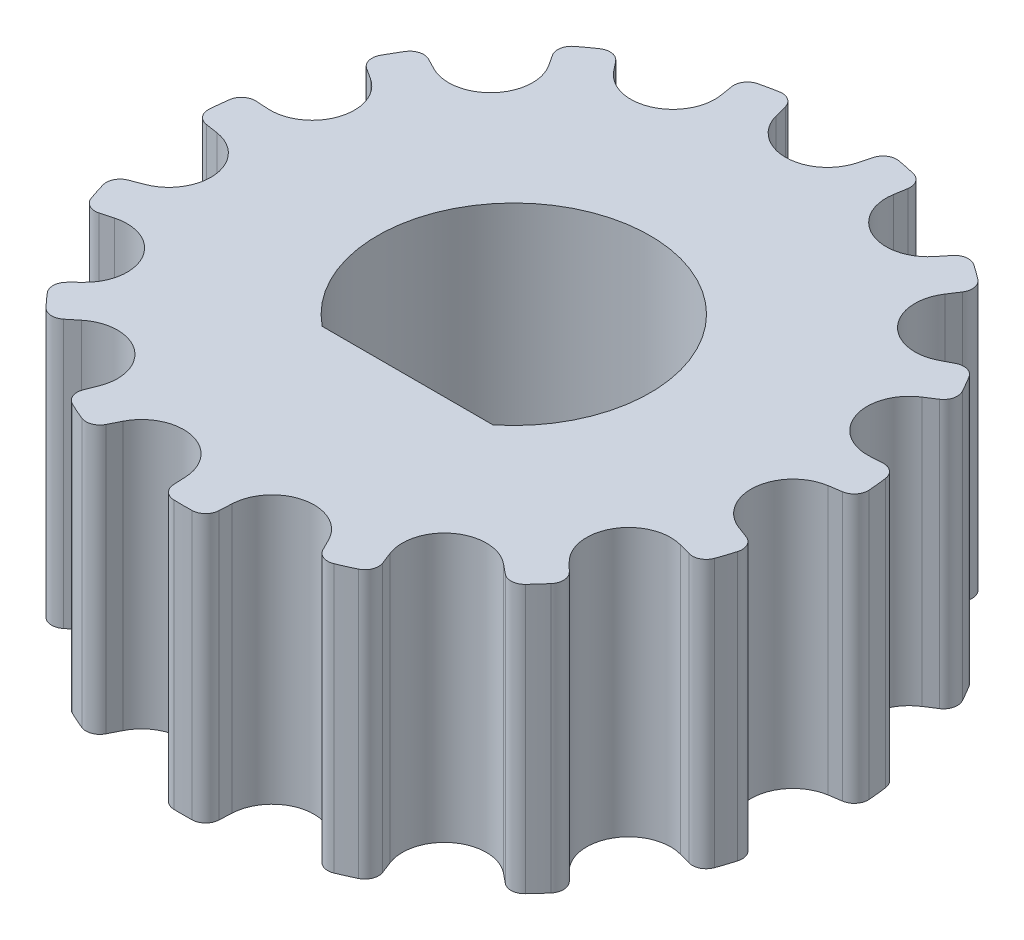
SolidWorks part; units mm, degrees
ref_plane "Front Plane" through (0, 0, 0) normal (0, 0, 1) x (1, 0, 0)
ref_plane "Top Plane" through (0, 0, 0) normal (0, 1, 0) x (1, 0, 0)
ref_plane "Right Plane" through (0, 0, 0) normal (1, 0, 0) x (0, 0, -1)
sketch "Sketch1" plane through (0, 0, 0) normal (0, 1, 0) x (1, 0, 0)
  circle A0 centre (0, 0) radius 7.162
  dimension "D1" = 14.3239
extrude "Boss-Extrude1" add sketch "Sketch1" along normal blind 5.8
sketch "Sketch2" plane through (0, 5.8, 0) normal (0, 1, 0) x (1, 0, 0)
  line L0 (0, 0) -> (0, 7.162) construction
  line L1 (-0.8799, 6.5598) -> (-0.95, 6.8255)
  line L2 (-2.913, 6.5428) -> (-2.913, 7.162)
  line L3 (-2.913, 7.162) -> (2.913, 7.162)
  line L4 (0.8799, 6.5598) -> (0.95, 6.8255)
  line L5 (2.913, 6.5428) -> (2.913, 7.162)
  circle A0 centre (0, 0) radius 7.162 construction
  arc A1 (0.8799, 6.5598) -> (-0.8799, 6.5598) centre (0, 6.792) cw
  arc A2 (-0.95, 6.8255) -> (-1.2943, 7.0441) centre (-1.2401, 6.749) ccw
  arc A4 (0.95, 6.8255) -> (1.2943, 7.0441) centre (1.2401, 6.749) cw
  arc A5 (-1.2943, 7.0441) -> (-2.913, 6.5428) centre (0, 0) ccw
  arc A6 (1.2943, 7.0441) -> (2.913, 6.5428) centre (0, 0) cw
  point P11 (0, 7.162)
  point P19 (0, 5.882)
  dimension "D3" = 0.3
  dimension "D5" = 0.91
  dimension "D2" = 0.95
  dimension "D4" = 1.28
  dimension "D6" = 24
extrude "Cut-Extrude1" cut sketch "Sketch2" against normal through all
pattern_circular "CirPattern1" count 15 over 360 about axis through (0, 0, 0) along (0, 1, 0) of "Cut-Extrude1"
sketch "Sketch3" plane through (0, 0, 0) normal (0, -1, 0) x (1, 0, 0)
  line L0 (1.8473, 2.3) -> (-1.8473, 2.3)
  arc A0 (-1.8473, 2.3) -> (1.8473, 2.3) centre (0, 0) ccw
  dimension "D1" = 5.9
  dimension "D2" = 2.3
extrude "Cut-Extrude2" cut sketch "Sketch3" against normal through all
sketch "Sketch5" plane through (0, 0, 0) normal (0, -1, 0) x (1, 0, 0)
  line L60 (5.4179, -3.8244) -> (5.6623, -3.9501)
  line L61 (6.252, -2.9286) -> (6.021, -2.7798)
  line L62 (6.505, -1.2901) -> (6.7794, -1.3055)
  line L63 (6.9027, -0.1325) -> (6.6311, -0.0906)
  line L64 (6.4674, 1.4673) -> (6.7243, 1.5648)
  line L65 (6.3598, 2.6865) -> (6.0946, 2.6144)
  line L66 (5.3115, 3.9709) -> (5.5065, 4.1645)
  line L67 (4.7173, 5.041) -> (4.5044, 4.8673)
  line L68 (3.2371, 5.788) -> (3.3366, 6.0442)
  line L69 (2.2591, 6.5239) -> (2.1352, 6.2786)
  line L70 (0.6031, 6.6042) -> (0.5897, 6.8787)
  line L71 (-0.5897, 6.8787) -> (-0.6031, 6.6042)
  line L72 (-2.1352, 6.2786) -> (-2.2591, 6.5239)
  line L73 (-3.3366, 6.0442) -> (-3.2371, 5.788)
  line L74 (-4.5044, 4.8673) -> (-4.7173, 5.041)
  line L75 (-5.5065, 4.1645) -> (-5.3115, 3.9709)
  line L76 (-6.0946, 2.6144) -> (-6.3598, 2.6865)
  line L77 (-6.7243, 1.5648) -> (-6.4674, 1.4673)
  line L78 (-6.6311, -0.0906) -> (-6.9027, -0.1325)
  line L79 (-6.7794, -1.3055) -> (-6.505, -1.2901)
  line L80 (-6.021, -2.7798) -> (-6.252, -2.9286)
  line L81 (-5.6623, -3.9501) -> (-5.4179, -3.8244)
  line L82 (-4.3698, -4.9885) -> (-4.5203, -5.2184)
  line L83 (-3.5661, -5.9117) -> (-3.394, -5.6974)
  line L84 (-1.963, -6.3345) -> (-2.007, -6.6058)
  line L85 (-0.8533, -6.851) -> (-0.7832, -6.5853)
  line L86 (0.7832, -6.5853) -> (0.8533, -6.851)
  line L87 (2.007, -6.6058) -> (1.963, -6.3345)
  line L88 (3.394, -5.6974) -> (3.5661, -5.9117)
  line L89 (4.5203, -5.2184) -> (4.3698, -4.9885)
  line L90 (5.4179, -3.8244) -> (5.6623, -3.9501)
  line L91 (6.252, -2.9286) -> (6.021, -2.7798)
  line L92 (6.505, -1.2901) -> (6.7794, -1.3055)
  line L93 (6.9027, -0.1325) -> (6.6311, -0.0906)
  line L94 (6.4674, 1.4673) -> (6.7243, 1.5648)
  line L95 (6.3598, 2.6865) -> (6.0946, 2.6144)
  line L96 (5.3115, 3.9709) -> (5.5065, 4.1645)
  line L97 (4.7173, 5.041) -> (4.5044, 4.8673)
  line L98 (3.2371, 5.788) -> (3.3366, 6.0442)
  line L99 (2.2591, 6.5239) -> (2.1352, 6.2786)
  line L100 (0.6031, 6.6042) -> (0.5897, 6.8787)
  line L101 (-0.5897, 6.8787) -> (-0.6031, 6.6042)
  line L102 (-2.1352, 6.2786) -> (-2.2591, 6.5239)
  line L103 (-3.3366, 6.0442) -> (-3.2371, 5.788)
  line L104 (-4.5044, 4.8673) -> (-4.7173, 5.041)
  line L105 (-5.5065, 4.1645) -> (-5.3115, 3.9709)
  line L106 (-6.0946, 2.6144) -> (-6.3598, 2.6865)
  line L107 (-6.7243, 1.5648) -> (-6.4674, 1.4673)
  line L108 (-6.6311, -0.0906) -> (-6.9027, -0.1325)
  line L109 (-6.7794, -1.3055) -> (-6.505, -1.2901)
  line L110 (-6.021, -2.7798) -> (-6.252, -2.9286)
  line L111 (-5.6623, -3.9501) -> (-5.4179, -3.8244)
  line L112 (-4.3698, -4.9885) -> (-4.5203, -5.2184)
  line L113 (-3.5661, -5.9117) -> (-3.394, -5.6974)
  line L114 (-1.963, -6.3345) -> (-2.007, -6.6058)
  line L115 (-0.8533, -6.851) -> (-0.7832, -6.5853)
  line L116 (0.7832, -6.5853) -> (0.8533, -6.851)
  line L117 (2.007, -6.6058) -> (1.963, -6.3345)
  line L118 (3.394, -5.6974) -> (3.5661, -5.9117)
  line L119 (4.5203, -5.2184) -> (4.3698, -4.9885)
  circle A60 centre (0, 0) radius 3.9038
  arc A120 (5.6623, -3.9501) -> (6.186, -3.8039) centre (5.8452, -3.5944) ccw
  arc A121 (6.186, -3.8039) -> (6.3873, -3.4553) centre (0, 0) ccw
  arc A122 (6.3873, -3.4553) -> (6.252, -2.9286) centre (6.0355, -3.2649) ccw
  arc A123 (6.505, -1.2901) -> (6.021, -2.7798) centre (6.4595, -2.0988) ccw
  arc A124 (6.7794, -1.3055) -> (7.1984, -0.959) centre (6.8019, -0.9062) ccw
  arc A125 (7.1984, -0.959) -> (7.2405, -0.5586) centre (0, 0) ccw
  arc A126 (7.2405, -0.5586) -> (6.9027, -0.1325) centre (6.8416, -0.5278) ccw
  arc A127 (6.4674, 1.4673) -> (6.6311, -0.0906) centre (6.7548, 0.71) ccw
  arc A128 (6.7243, 1.5648) -> (6.9661, 2.0518) centre (6.5824, 1.9387) ccw
  arc A129 (6.9661, 2.0518) -> (6.8417, 2.4347) centre (0, 0) ccw
  arc A130 (6.8417, 2.4347) -> (6.3598, 2.6865) centre (6.4648, 2.3006) ccw
  arc A131 (5.3115, 3.9709) -> (6.0946, 2.6144) centre (5.882, 3.396) ccw
  arc A132 (5.5065, 4.1645) -> (5.5293, 4.7077) centre (5.2248, 4.4484) ccw
  arc A133 (5.5293, 4.7077) -> (5.2599, 5.0069) centre (0, 0) ccw
  arc A134 (5.2599, 5.0069) -> (4.7173, 5.041) centre (4.9702, 4.7312) ccw
  arc A135 (3.2371, 5.788) -> (4.5044, 4.8673) centre (3.9922, 5.4948) ccw
  arc A136 (3.3366, 6.0442) -> (3.1365, 6.5497) centre (2.9637, 6.1889) ccw
  arc A137 (3.1365, 6.5497) -> (2.7687, 6.7135) centre (0, 0) ccw
  arc A138 (2.7687, 6.7135) -> (2.2591, 6.5239) centre (2.6162, 6.3437) ccw
  arc A139 (0.6031, 6.6042) -> (2.1352, 6.2786) centre (1.4121, 6.6436) ccw
  arc A140 (0.5897, 6.8787) -> (0.2013, 7.2592) centre (0.1902, 6.8593) ccw
  arc A141 (0.2013, 7.2592) -> (-0.2013, 7.2592) centre (0, 0) ccw
  arc A142 (-0.2013, 7.2592) -> (-0.5897, 6.8787) centre (-0.1902, 6.8593) ccw
  arc A143 (-2.1352, 6.2786) -> (-0.6031, 6.6042) centre (-1.4121, 6.6436) ccw
  arc A144 (-2.2591, 6.5239) -> (-2.7687, 6.7135) centre (-2.6162, 6.3437) ccw
  arc A145 (-2.7687, 6.7135) -> (-3.1365, 6.5497) centre (0, 0) ccw
  arc A146 (-3.1365, 6.5497) -> (-3.3366, 6.0442) centre (-2.9637, 6.1889) ccw
  arc A147 (-4.5044, 4.8673) -> (-3.2371, 5.788) centre (-3.9922, 5.4948) ccw
  arc A148 (-4.7173, 5.041) -> (-5.2599, 5.0069) centre (-4.9702, 4.7312) ccw
  arc A149 (-5.2599, 5.0069) -> (-5.5293, 4.7077) centre (0, 0) ccw
  arc A150 (-5.5293, 4.7077) -> (-5.5065, 4.1645) centre (-5.2248, 4.4484) ccw
  arc A151 (-6.0946, 2.6144) -> (-5.3115, 3.9709) centre (-5.882, 3.396) ccw
  arc A152 (-6.3598, 2.6865) -> (-6.8417, 2.4347) centre (-6.4648, 2.3006) ccw
  arc A153 (-6.8417, 2.4347) -> (-6.9661, 2.0518) centre (0, 0) ccw
  arc A154 (-6.9661, 2.0518) -> (-6.7243, 1.5648) centre (-6.5824, 1.9387) ccw
  arc A155 (-6.6311, -0.0906) -> (-6.4674, 1.4673) centre (-6.7548, 0.71) ccw
  arc A156 (-6.9027, -0.1325) -> (-7.2405, -0.5586) centre (-6.8416, -0.5278) ccw
  arc A157 (-7.2405, -0.5586) -> (-7.1984, -0.959) centre (0, 0) ccw
  arc A158 (-7.1984, -0.959) -> (-6.7794, -1.3055) centre (-6.8019, -0.9062) ccw
  arc A159 (-6.021, -2.7798) -> (-6.505, -1.2901) centre (-6.4595, -2.0988) ccw
  arc A160 (-6.252, -2.9286) -> (-6.3873, -3.4553) centre (-6.0355, -3.2649) ccw
  arc A161 (-6.3873, -3.4553) -> (-6.186, -3.8039) centre (0, 0) ccw
  arc A162 (-6.186, -3.8039) -> (-5.6623, -3.9501) centre (-5.8452, -3.5944) ccw
  arc A163 (-4.3698, -4.9885) -> (-5.4179, -3.8244) centre (-5.0474, -4.5447) ccw
  arc A164 (-4.5203, -5.2184) -> (-4.4297, -5.7545) centre (-4.1857, -5.4375) ccw
  arc A165 (-4.4297, -5.7545) -> (-4.104, -5.9911) centre (0, 0) ccw
  arc A166 (-4.104, -5.9911) -> (-3.5661, -5.9117) centre (-3.8779, -5.6611) ccw
  arc A167 (-1.963, -6.3345) -> (-3.394, -5.6974) centre (-2.7625, -6.2048) ccw
  arc A168 (-2.007, -6.6058) -> (-1.7062, -7.0587) centre (-1.6122, -6.6699) ccw
  arc A169 (-1.7062, -7.0587) -> (-1.3124, -7.1424) centre (0, 0) ccw
  arc A170 (-1.3124, -7.1424) -> (-0.8533, -6.851) centre (-1.2401, -6.749) ccw
  arc A171 (0.7832, -6.5853) -> (-0.7832, -6.5853) centre (0, -6.792) ccw
  arc A172 (0.8533, -6.851) -> (1.3124, -7.1424) centre (1.2401, -6.749) ccw
  arc A173 (1.3124, -7.1424) -> (1.7062, -7.0587) centre (0, 0) ccw
  arc A174 (1.7062, -7.0587) -> (2.007, -6.6058) centre (1.6122, -6.6699) ccw
  arc A175 (3.394, -5.6974) -> (1.963, -6.3345) centre (2.7625, -6.2048) ccw
  arc A176 (3.5661, -5.9117) -> (4.104, -5.9911) centre (3.8779, -5.6611) ccw
  arc A177 (4.104, -5.9911) -> (4.4297, -5.7545) centre (0, 0) ccw
  arc A178 (4.4297, -5.7545) -> (4.5203, -5.2184) centre (4.1857, -5.4375) ccw
  arc A179 (5.4179, -3.8244) -> (4.3698, -4.9885) centre (5.0474, -4.5447) ccw
  arc A180 (5.6623, -3.9501) -> (6.186, -3.8039) centre (5.8452, -3.5944) ccw
  arc A181 (6.186, -3.8039) -> (6.3873, -3.4553) centre (0, 0) ccw
  arc A182 (6.3873, -3.4553) -> (6.252, -2.9286) centre (6.0355, -3.2649) ccw
  arc A183 (6.505, -1.2901) -> (6.021, -2.7798) centre (6.4595, -2.0988) ccw
  arc A184 (6.7794, -1.3055) -> (7.1984, -0.959) centre (6.8019, -0.9062) ccw
  arc A185 (7.1984, -0.959) -> (7.2405, -0.5586) centre (0, 0) ccw
  arc A186 (7.2405, -0.5586) -> (6.9027, -0.1325) centre (6.8416, -0.5278) ccw
  arc A187 (6.4674, 1.4673) -> (6.6311, -0.0906) centre (6.7548, 0.71) ccw
  arc A188 (6.7243, 1.5648) -> (6.9661, 2.0518) centre (6.5824, 1.9387) ccw
  arc A189 (6.9661, 2.0518) -> (6.8417, 2.4347) centre (0, 0) ccw
  arc A190 (6.8417, 2.4347) -> (6.3598, 2.6865) centre (6.4648, 2.3006) ccw
  arc A191 (5.3115, 3.9709) -> (6.0946, 2.6144) centre (5.882, 3.396) ccw
  arc A192 (5.5065, 4.1645) -> (5.5293, 4.7077) centre (5.2248, 4.4484) ccw
  arc A193 (5.5293, 4.7077) -> (5.2599, 5.0069) centre (0, 0) ccw
  arc A194 (5.2599, 5.0069) -> (4.7173, 5.041) centre (4.9702, 4.7312) ccw
  arc A195 (3.2371, 5.788) -> (4.5044, 4.8673) centre (3.9922, 5.4948) ccw
  arc A196 (3.3366, 6.0442) -> (3.1365, 6.5497) centre (2.9637, 6.1889) ccw
  arc A197 (3.1365, 6.5497) -> (2.7687, 6.7135) centre (0, 0) ccw
  arc A198 (2.7687, 6.7135) -> (2.2591, 6.5239) centre (2.6162, 6.3437) ccw
  arc A199 (0.6031, 6.6042) -> (2.1352, 6.2786) centre (1.4121, 6.6436) ccw
  arc A200 (0.5897, 6.8787) -> (0.2013, 7.2592) centre (0.1902, 6.8593) ccw
  arc A201 (0.2013, 7.2592) -> (-0.2013, 7.2592) centre (0, 0) ccw
  arc A202 (-0.2013, 7.2592) -> (-0.5897, 6.8787) centre (-0.1902, 6.8593) ccw
  arc A203 (-2.1352, 6.2786) -> (-0.6031, 6.6042) centre (-1.4121, 6.6436) ccw
  arc A204 (-2.2591, 6.5239) -> (-2.7687, 6.7135) centre (-2.6162, 6.3437) ccw
  arc A205 (-2.7687, 6.7135) -> (-3.1365, 6.5497) centre (0, 0) ccw
  arc A206 (-3.1365, 6.5497) -> (-3.3366, 6.0442) centre (-2.9637, 6.1889) ccw
  arc A207 (-4.5044, 4.8673) -> (-3.2371, 5.788) centre (-3.9922, 5.4948) ccw
  arc A208 (-4.7173, 5.041) -> (-5.2599, 5.0069) centre (-4.9702, 4.7312) ccw
  arc A209 (-5.2599, 5.0069) -> (-5.5293, 4.7077) centre (0, 0) ccw
  arc A210 (-5.5293, 4.7077) -> (-5.5065, 4.1645) centre (-5.2248, 4.4484) ccw
  arc A211 (-6.0946, 2.6144) -> (-5.3115, 3.9709) centre (-5.882, 3.396) ccw
  arc A212 (-6.3598, 2.6865) -> (-6.8417, 2.4347) centre (-6.4648, 2.3006) ccw
  arc A213 (-6.8417, 2.4347) -> (-6.9661, 2.0518) centre (0, 0) ccw
  arc A214 (-6.9661, 2.0518) -> (-6.7243, 1.5648) centre (-6.5824, 1.9387) ccw
  arc A215 (-6.6311, -0.0906) -> (-6.4674, 1.4673) centre (-6.7548, 0.71) ccw
  arc A216 (-6.9027, -0.1325) -> (-7.2405, -0.5586) centre (-6.8416, -0.5278) ccw
  arc A217 (-7.2405, -0.5586) -> (-7.1984, -0.959) centre (0, 0) ccw
  arc A218 (-7.1984, -0.959) -> (-6.7794, -1.3055) centre (-6.8019, -0.9062) ccw
  arc A219 (-6.021, -2.7798) -> (-6.505, -1.2901) centre (-6.4595, -2.0988) ccw
  arc A220 (-6.252, -2.9286) -> (-6.3873, -3.4553) centre (-6.0355, -3.2649) ccw
  arc A221 (-6.3873, -3.4553) -> (-6.186, -3.8039) centre (0, 0) ccw
  arc A222 (-6.186, -3.8039) -> (-5.6623, -3.9501) centre (-5.8452, -3.5944) ccw
  arc A223 (-4.3698, -4.9885) -> (-5.4179, -3.8244) centre (-5.0474, -4.5447) ccw
  arc A224 (-4.5203, -5.2184) -> (-4.4297, -5.7545) centre (-4.1857, -5.4375) ccw
  arc A225 (-4.4297, -5.7545) -> (-4.104, -5.9911) centre (0, 0) ccw
  arc A226 (-4.104, -5.9911) -> (-3.5661, -5.9117) centre (-3.8779, -5.6611) ccw
  arc A227 (-1.963, -6.3345) -> (-3.394, -5.6974) centre (-2.7625, -6.2048) ccw
  arc A228 (-2.007, -6.6058) -> (-1.7062, -7.0587) centre (-1.6122, -6.6699) ccw
  arc A229 (-1.7062, -7.0587) -> (-1.3124, -7.1424) centre (0, 0) ccw
  arc A230 (-1.3124, -7.1424) -> (-0.8533, -6.851) centre (-1.2401, -6.749) ccw
  arc A231 (0.7832, -6.5853) -> (-0.7832, -6.5853) centre (0, -6.792) ccw
  arc A232 (0.8533, -6.851) -> (1.3124, -7.1424) centre (1.2401, -6.749) ccw
  arc A233 (1.3124, -7.1424) -> (1.7062, -7.0587) centre (0, 0) ccw
  arc A234 (1.7062, -7.0587) -> (2.007, -6.6058) centre (1.6122, -6.6699) ccw
  arc A235 (3.394, -5.6974) -> (1.963, -6.3345) centre (2.7625, -6.2048) ccw
  arc A236 (3.5661, -5.9117) -> (4.104, -5.9911) centre (3.8779, -5.6611) ccw
  arc A237 (4.104, -5.9911) -> (4.4297, -5.7545) centre (0, 0) ccw
  arc A238 (4.4297, -5.7545) -> (4.5203, -5.2184) centre (4.1857, -5.4375) ccw
  arc A239 (5.4179, -3.8244) -> (4.3698, -4.9885) centre (5.0474, -4.5447) ccw
  dimension "D1" = 0.1
extrude "Boss-Extrude2" [suppressed] add sketch "Sketch5" against normal up to surface (5.8 mm away)
sketch "Sketch6" plane through (0, 5.8, 0) normal (0, 1, 0) x (1, 0, 0)
  circle A0 centre (0, -10) radius 2.5
  dimension "D1" = 5
  dimension "D2" = 10
extrude "Cut-Extrude3" [suppressed] cut sketch "Sketch6" against normal through all
equation "\"smallPulleyTeeth\"= 15"
equation "\"largePulleyTeeth\"= 30"
equation "\"eighthThick\"= 2.9mm"
equation "\"D1@Sketch1\"=3*\"smallPulleyTeeth\"/pi"
equation "\"D1@Boss-Extrude1\" = \"eighthThick\" * 2"
equation "\"D6@Sketch2\"=360/\"smallPulleyTeeth\""
equation "\"quarterThick\"=5.9mm"
equation "\"D1@CirPattern1\"=\"smallPulleyTeeth\""
equation "\"sixteenthThick\"= 1.7mm"
equation "\"OD\"= 145mm"
equation "\"puckAngle\"= 60.5deg"
equation "\"puckDiam\"= 76.5mm"
equation "\"axlePress\"= 5.9mm"
equation "\"press\"= 0.2mm"
equation "\"wheelClear\"= 0.3mm"
equation "\"10-32clear\"= 4.5mm"
equation "\"6-32clear\"= 3.3mm"
equation "\"8-32clear\"= 4.0mm"
equation "\"wheelHeight\"= 22mm"
equation "\"D1@Sketch3\"=\"axlePress\""
